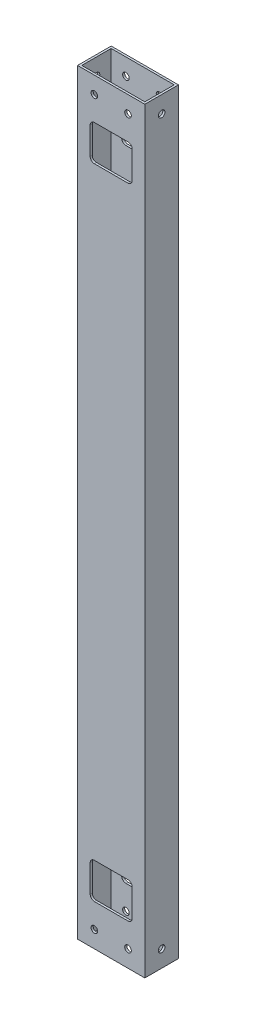
SolidWorks part; units mm, degrees
material "6061-T6 (SS)"
ref_plane "Front Plane" through (0, 0, 0) normal (0, 0, 1) x (1, 0, 0)
ref_plane "Top Plane" through (0, 0, 0) normal (0, 1, 0) x (1, 0, 0)
ref_plane "Right Plane" through (0, 0, 0) normal (1, 0, 0) x (0, 0, -1)
sketch "Sketch1" plane through (0, 0, 0) normal (0, 0, 1) x (1, 0, 0)
  line L1 (-25.4, -285.75) -> (25.4, -285.75)
  line L2 (-25.4, -285.75) -> (-25.4, 285.75)
  line L3 (-25.4, 285.75) -> (25.4, 285.75)
  line L4 (25.4, -285.75) -> (25.4, 285.75)
  line L5 (-25.4, -285.75) -> (25.4, 285.75) construction
  line L6 (-25.4, 285.75) -> (25.4, -285.75) construction
  point P0 (0, 0)
  dimension "D1" = 50.8
  dimension "D2" = 571.5
extrude "Boss-Extrude1" add sketch "Sketch1" along normal mid plane 25.4
shell "Shell1" thickness 1.5875
sketch "Sketch2" plane through (0, 0, 0) normal (0, 0, 1) x (1, 0, 0)
  line L0 (-25.4, 285.75) -> (-25.4, -285.75) construction
  line L1 (-25.4, -285.75) -> (25.4, -285.75) construction
  line L2 (-25.4, 0) -> (25.4, 0) construction
  line L3 (25.4, -285.75) -> (25.4, 285.75) construction
  circle A0 centre (-12.7, -273.05) radius 2.4892
  circle A1 centre (12.7, -273.05) radius 2.4892
  circle A2 centre (12.7, 273.05) radius 2.4892
  circle A3 centre (-12.7, 273.05) radius 2.4892
  dimension "D1" = 4.9784
  dimension "D3" = 25.4
  dimension "D2" = 12.7
  dimension "D4" = 12.7
extrude "Cut-Extrude1" cut sketch "Sketch2" against normal through all both and the other way through all
sketch "Sketch3" plane through (0, 0, 0) normal (1, 0, 0) x (0, 0, -1)
  line L0 (-12.7, -285.75) -> (12.7, -285.75) construction
  line L1 (-12.7, 285.75) -> (12.7, 285.75) construction
  circle A0 centre (0, -273.05) radius 2.4892
  circle A1 centre (0, 273.05) radius 2.4892
  point P6 (0, -285.75)
  point P9 (0, 285.75)
  dimension "D1" = 4.9784
  dimension "D2" = 12.7
  dimension "D3" = 12.7
extrude "Cut-Extrude2" cut sketch "Sketch3" against normal through all both and the other way through all
sketch "Sketch4" plane through (0, 0, 0) normal (0, 0, 1) x (1, 0, 0)
  line L0 (25.4, 285.75) -> (-25.4, 285.75) construction
  line L1 (-15.875, 254.7937) -> (15.875, 254.7937)
  line L2 (-15.875, 254.7937) -> (-15.875, 227.8062)
  line L3 (-15.875, 227.8062) -> (15.875, 227.8062)
  line L4 (15.875, 254.7937) -> (15.875, 227.8062)
  point P6 (0, 285.75)
  point P7 (0, 254.7937)
  dimension "D1" = 30.9562
  dimension "D2" = 31.75
  dimension "D3" = 26.9875
extrude "Cut-Extrude3" cut sketch "Sketch4" against normal through all both and the other way through all
fillet "Fillet1" radius 3.175 4 edges at (-15.875, 254.7937, -11.9062) (15.875, 227.8062, -11.9062) (-15.875, 227.8062, -11.9062) (15.875, 254.7937, -11.9062)
ref_plane "Plane1" through (0, 0, 0) normal (0, 1, 0) x (1, 0, 0)
mirror "Mirror1" about plane through (0, 0, 0) normal (0, 1, 0) of "Fillet1", "Cut-Extrude3"
fillet "Fillet2" radius 3.175 8 edges at (15.875, 227.8062, 11.9062) (15.875, 254.7937, 11.9062) (-15.875, 254.7937, 11.9062) (-15.875, 227.8062, 11.9062) (15.875, -227.8062, 11.9062) (15.875, -254.7937, 11.9062) (-15.875, -227.8062, 11.9062) (-15.875, -254.7937, 11.9062)
